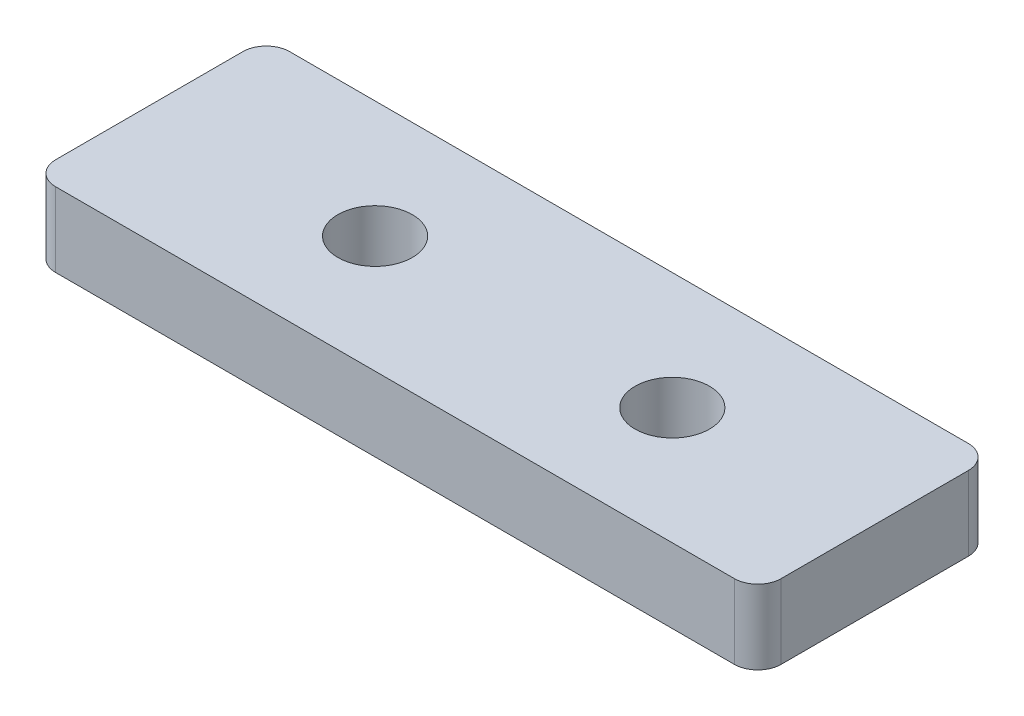
SolidWorks part; units mm, degrees
ref_plane "Front Plane" through (0, 0, 0) normal (0, 0, 1) x (1, 0, 0)
ref_plane "Top Plane" through (0, 0, 0) normal (0, 1, 0) x (1, 0, 0)
ref_plane "Right Plane" through (0, 0, 0) normal (1, 0, 0) x (0, 0, -1)
sketch "Sketch1" plane through (0, 0, 0) normal (0, 1, 0) x (1, 0, 0)
  line L0 (0, 0) -> (12.7, 0) construction
  line L5 (-3.65, 5) -> (16.35, 5)
  line L6 (-3.65, 5) -> (-3.65, -5)
  line L7 (-3.65, -5) -> (16.35, -5)
  line L8 (16.35, 5) -> (16.35, -5)
  line L10 (16.35, 5) -> (21.35, 5)
  line L11 (16.35, 5) -> (16.35, -5)
  line L12 (16.35, -5) -> (21.35, -5)
  line L13 (21.35, 5) -> (21.35, -5)
  line L14 (-3.65, 5) -> (-9.65, 5)
  line L15 (-3.65, 5) -> (-3.65, -5)
  line L16 (-3.65, -5) -> (-9.65, -5)
  line L17 (-9.65, 5) -> (-9.65, -5)
  circle A0 centre (0, 0) radius 1.59
  circle A1 centre (12.7, 0) radius 1.59
  point P9 (16.35, 0)
  point P10 (6.35, 0)
  point P11 (6.35, 5)
  dimension "D1" = 3.18
  dimension "D2" = 12.7
  dimension "D3" = 10
  dimension "D4" = 20
  dimension "D5" = 5
  dimension "D6" = 6
extrude "Boss-Extrude1" add sketch "Sketch1" along normal blind 3.175
fillet "Fillet1" radius 1 4 edges at (21.35, 1.5875, 5) (21.35, 1.5875, -5) (-9.65, 1.5875, 5) (-9.65, 1.5875, -5)
